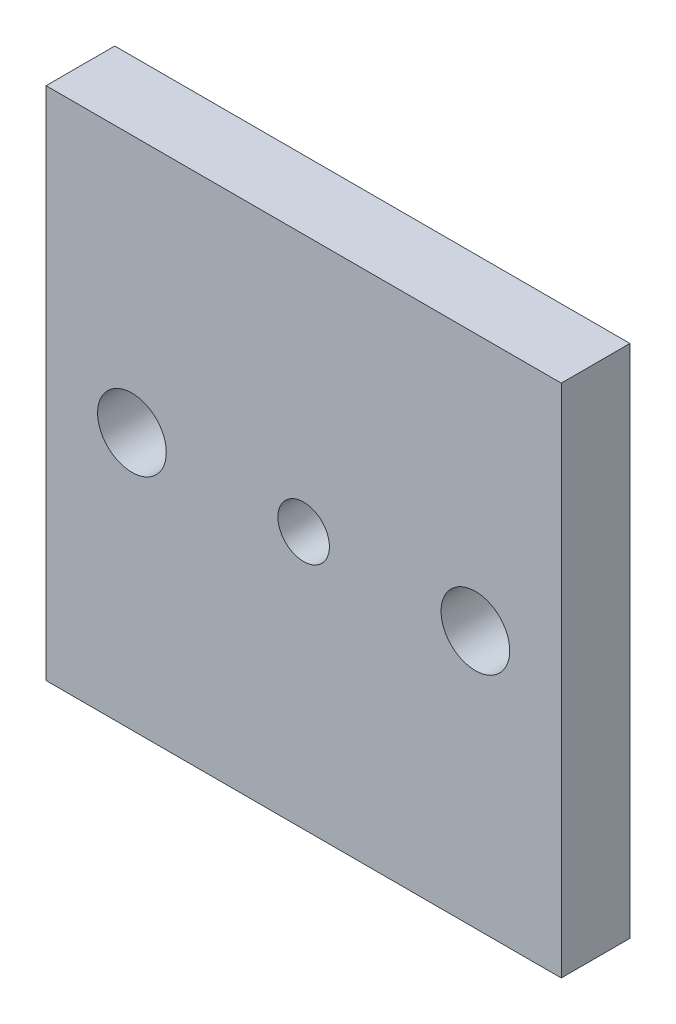
SolidWorks part; units mm, degrees
ref_plane "Front Plane" through (0, 0, 0) normal (0, 0, 1) x (1, 0, 0)
ref_plane "Top Plane" through (0, 0, 0) normal (0, 1, 0) x (1, 0, 0)
ref_plane "Right Plane" through (0, 0, 0) normal (1, 0, 0) x (0, 0, -1)
sketch "Sketch1" plane through (0, 0, 0) normal (0, 0, 1) x (1, 0, 0)
  line L0 (0, -15) -> (30, -15) construction
  line L1 (0, 0) -> (30, 0)
  line L2 (0, 0) -> (0, -30)
  line L3 (0, -30) -> (30, -30)
  line L4 (30, 0) -> (30, -30)
  circle A0 centre (15, -15) radius 12.5
  circle A1 centre (15, -15) radius 1.5
  circle A2 centre (5, -15) radius 2
  circle A3 centre (25, -15) radius 2
  dimension "D4" = 25
  dimension "D6" = 3
  dimension "D9" = 4
  dimension "D10" = 4
  dimension "D1" = 30
  dimension "D2" = 30
  dimension "D3" = 15
  dimension "D5" = 15
  dimension "D7" = 20
  dimension "D8" = 10
extrude "Boss-Extrude1" add sketch "Sketch1" along normal blind 4 contours L2 L0 A0 L4 L1 | L0 L2 L3 L4 A0 | L0 A0 A3 A1 A2 | A0 L0 A2 A1 A3
